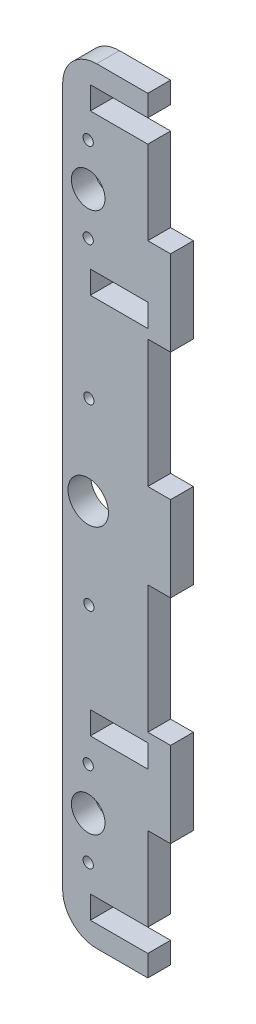
SolidWorks part; units mm, degrees
ref_plane "Front Plane" through (0, 0, 0) normal (0, 0, 1) x (1, 0, 0)
ref_plane "Top Plane" through (0, 0, 0) normal (0, 1, 0) x (1, 0, 0)
ref_plane "Right Plane" through (0, 0, 0) normal (1, 0, 0) x (0, 0, -1)
sketch "Model" plane through (0, 0, 0) normal (0, 0, 1) x (1, 0, 0)
  line L236 (20, 175) -> (20, 180)
  line L237 (6.5, 175) -> (20, 175)
  line L238 (6.5, 169.65) -> (6.5, 175)
  line L239 (20, 169.65) -> (6.5, 169.65)
  line L240 (20, 150) -> (20, 169.65)
  line L241 (25.35, 150) -> (20, 150)
  line L242 (25.35, 130) -> (25.35, 150)
  line L243 (20, 130) -> (25.35, 130)
  line L244 (20, 100) -> (20, 130)
  line L245 (25.35, 100) -> (20, 100)
  line L246 (25.35, 80) -> (25.35, 100)
  line L247 (20, 80) -> (25.35, 80)
  line L248 (20, 50) -> (20, 80)
  line L249 (25.35, 50) -> (20, 50)
  line L250 (25.35, 30) -> (25.35, 50)
  line L251 (20, 30) -> (25.35, 30)
  line L252 (20, 10.35) -> (20, 30)
  line L253 (6.5, 10.35) -> (20, 10.35)
  line L254 (6.5, 5) -> (6.5, 10.35)
  line L255 (20, 5) -> (6.5, 5)
  line L256 (20, 0) -> (20, 5)
  line L257 (8, 0) -> (20, 0)
  line L258 (0, 172) -> (0, 8)
  line L259 (20, 180) -> (8, 180)
  line L260 (6.5, 47.85) -> (20, 47.85)
  line L261 (6.5, 42.5) -> (6.5, 47.85)
  line L262 (20, 42.5) -> (6.5, 42.5)
  line L263 (20, 47.85) -> (20, 42.5)
  line L264 (6.5, 137.5) -> (20, 137.5)
  line L265 (6.5, 132.15) -> (6.5, 137.5)
  line L266 (20, 132.15) -> (6.5, 132.15)
  line L267 (20, 137.5) -> (20, 132.15)
  circle A20 centre (6, 90) radius 4.75
  circle A21 centre (6, 26.5) radius 3.95
  arc A22 (0, 8) -> (8, 0) centre (8, 8) ccw
  arc A23 (8, 180) -> (0, 172) centre (8, 172) ccw
  circle A24 centre (6, 153.5) radius 3.95
  circle A25 centre (6.16, 111) radius 1.2
  circle A26 centre (6.16, 69) radius 1.2
  circle A27 centre (6, 36.5) radius 1.2
  circle A28 centre (6, 16.5) radius 1.2
  circle A29 centre (6, 143.5) radius 1.2
  circle A30 centre (6, 163.5) radius 1.2
extrude "Boss-Extrude1" add sketch "Model" along normal blind 5.35
